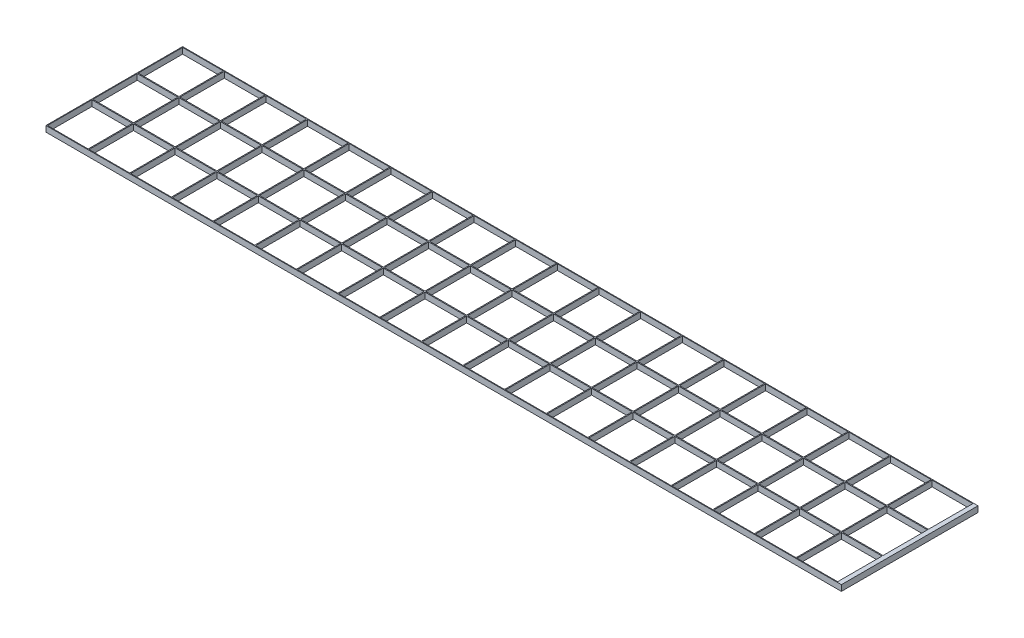
SolidWorks part; units mm, degrees
ref_plane "Front Plane" through (0, 0, 0) normal (0, 0, 1) x (1, 0, 0)
ref_plane "Top Plane" through (0, 0, 0) normal (0, 1, 0) x (1, 0, 0)
ref_plane "Right Plane" through (0, 0, 0) normal (1, 0, 0) x (0, 0, -1)
sketch "Sketch1" plane through (0, 0, 0) normal (0, 1, 0) x (1, 0, 0)
  line L1 (0, 0) -> (431.8, 0)
  line L2 (0, 0) -> (0, 74.168)
  line L3 (0, 74.168) -> (431.8, 74.168)
  line L4 (431.8, 0) -> (431.8, 74.168)
  dimension "D1" = 431.8
  dimension "D2" = 74.168
extrude "Boss-Extrude1" add sketch "Sketch1" along normal blind 3.175
sketch "Sketch2" plane through (0, 3.175, 0) normal (0, 1, 0) x (1, 0, 0)
  line L0 (431.8, 74.168) -> (0, 74.168) construction
  line L1 (0.381, 73.787) -> (22.479, 73.787)
  line L2 (0.381, 73.787) -> (0.381, 49.657)
  line L3 (0.381, 49.657) -> (22.479, 49.657)
  line L4 (22.479, 73.787) -> (22.479, 49.657)
  line L5 (0, 74.168) -> (0, 0) construction
  line L6 (0.381, 25.019) -> (22.479, 25.019)
  line L7 (22.479, 49.149) -> (22.479, 25.019)
  line L8 (0.381, 49.149) -> (0.381, 25.019)
  line L9 (0.381, 49.149) -> (22.479, 49.149)
  line L10 (0.381, 0.381) -> (22.479, 0.381)
  line L11 (22.479, 24.511) -> (22.479, 0.381)
  line L12 (0.381, 24.511) -> (0.381, 0.381)
  line L13 (0.381, 24.511) -> (22.479, 24.511)
  line L14 (22.987, 49.657) -> (45.085, 49.657)
  line L15 (45.085, 73.787) -> (45.085, 49.657)
  line L16 (22.987, 73.787) -> (22.987, 49.657)
  line L17 (22.987, 73.787) -> (45.085, 73.787)
  line L18 (22.987, 49.149) -> (22.987, 25.019)
  line L19 (45.085, 49.149) -> (45.085, 25.019)
  line L20 (22.987, 49.149) -> (45.085, 49.149)
  line L21 (22.987, 25.019) -> (45.085, 25.019)
  line L22 (22.987, 24.511) -> (45.085, 24.511)
  line L23 (22.987, 24.511) -> (22.987, 0.381)
  line L24 (45.085, 24.511) -> (45.085, 0.381)
  line L25 (22.987, 0.381) -> (45.085, 0.381)
  line L26 (45.593, 49.657) -> (67.691, 49.657)
  line L27 (67.691, 73.787) -> (67.691, 49.657)
  line L28 (45.593, 73.787) -> (45.593, 49.657)
  line L29 (45.593, 73.787) -> (67.691, 73.787)
  line L30 (45.593, 49.149) -> (45.593, 25.019)
  line L31 (67.691, 49.149) -> (67.691, 25.019)
  line L32 (45.593, 49.149) -> (67.691, 49.149)
  line L33 (45.593, 25.019) -> (67.691, 25.019)
  line L34 (45.593, 24.511) -> (67.691, 24.511)
  line L35 (45.593, 24.511) -> (45.593, 0.381)
  line L36 (67.691, 24.511) -> (67.691, 0.381)
  line L37 (45.593, 0.381) -> (67.691, 0.381)
  line L38 (68.199, 49.657) -> (90.297, 49.657)
  line L39 (90.297, 73.787) -> (90.297, 49.657)
  line L40 (68.199, 73.787) -> (68.199, 49.657)
  line L41 (68.199, 73.787) -> (90.297, 73.787)
  line L42 (68.199, 49.149) -> (68.199, 25.019)
  line L43 (90.297, 49.149) -> (90.297, 25.019)
  line L44 (68.199, 49.149) -> (90.297, 49.149)
  line L45 (68.199, 25.019) -> (90.297, 25.019)
  line L46 (68.199, 24.511) -> (90.297, 24.511)
  line L47 (68.199, 24.511) -> (68.199, 0.381)
  line L48 (90.297, 24.511) -> (90.297, 0.381)
  line L49 (68.199, 0.381) -> (90.297, 0.381)
  line L50 (90.805, 49.657) -> (112.903, 49.657)
  line L51 (112.903, 73.787) -> (112.903, 49.657)
  line L52 (90.805, 73.787) -> (90.805, 49.657)
  line L53 (90.805, 73.787) -> (112.903, 73.787)
  line L54 (90.805, 49.149) -> (90.805, 25.019)
  line L55 (112.903, 49.149) -> (112.903, 25.019)
  line L56 (90.805, 49.149) -> (112.903, 49.149)
  line L57 (90.805, 25.019) -> (112.903, 25.019)
  line L58 (90.805, 24.511) -> (112.903, 24.511)
  line L59 (90.805, 24.511) -> (90.805, 0.381)
  line L60 (112.903, 24.511) -> (112.903, 0.381)
  line L61 (90.805, 0.381) -> (112.903, 0.381)
  line L62 (113.411, 49.657) -> (135.509, 49.657)
  line L63 (135.509, 73.787) -> (135.509, 49.657)
  line L64 (113.411, 73.787) -> (113.411, 49.657)
  line L65 (113.411, 73.787) -> (135.509, 73.787)
  line L66 (113.411, 49.149) -> (113.411, 25.019)
  line L67 (135.509, 49.149) -> (135.509, 25.019)
  line L68 (113.411, 49.149) -> (135.509, 49.149)
  line L69 (113.411, 25.019) -> (135.509, 25.019)
  line L70 (113.411, 24.511) -> (135.509, 24.511)
  line L71 (113.411, 24.511) -> (113.411, 0.381)
  line L72 (135.509, 24.511) -> (135.509, 0.381)
  line L73 (113.411, 0.381) -> (135.509, 0.381)
  line L74 (136.017, 49.657) -> (158.115, 49.657)
  line L75 (158.115, 73.787) -> (158.115, 49.657)
  line L76 (136.017, 73.787) -> (136.017, 49.657)
  line L77 (136.017, 73.787) -> (158.115, 73.787)
  line L78 (136.017, 49.149) -> (136.017, 25.019)
  line L79 (158.115, 49.149) -> (158.115, 25.019)
  line L80 (136.017, 49.149) -> (158.115, 49.149)
  line L81 (136.017, 25.019) -> (158.115, 25.019)
  line L82 (136.017, 24.511) -> (158.115, 24.511)
  line L83 (136.017, 24.511) -> (136.017, 0.381)
  line L84 (158.115, 24.511) -> (158.115, 0.381)
  line L85 (136.017, 0.381) -> (158.115, 0.381)
  line L86 (158.623, 49.657) -> (180.721, 49.657)
  line L87 (180.721, 73.787) -> (180.721, 49.657)
  line L88 (158.623, 73.787) -> (158.623, 49.657)
  line L89 (158.623, 73.787) -> (180.721, 73.787)
  line L90 (158.623, 49.149) -> (158.623, 25.019)
  line L91 (180.721, 49.149) -> (180.721, 25.019)
  line L92 (158.623, 49.149) -> (180.721, 49.149)
  line L93 (158.623, 25.019) -> (180.721, 25.019)
  line L94 (158.623, 24.511) -> (180.721, 24.511)
  line L95 (158.623, 24.511) -> (158.623, 0.381)
  line L96 (180.721, 24.511) -> (180.721, 0.381)
  line L97 (158.623, 0.381) -> (180.721, 0.381)
  line L98 (181.229, 49.657) -> (203.327, 49.657)
  line L99 (203.327, 73.787) -> (203.327, 49.657)
  line L100 (181.229, 73.787) -> (181.229, 49.657)
  line L101 (181.229, 73.787) -> (203.327, 73.787)
  line L102 (181.229, 49.149) -> (181.229, 25.019)
  line L103 (203.327, 49.149) -> (203.327, 25.019)
  line L104 (181.229, 49.149) -> (203.327, 49.149)
  line L105 (181.229, 25.019) -> (203.327, 25.019)
  line L106 (181.229, 24.511) -> (203.327, 24.511)
  line L107 (181.229, 24.511) -> (181.229, 0.381)
  line L108 (203.327, 24.511) -> (203.327, 0.381)
  line L109 (181.229, 0.381) -> (203.327, 0.381)
  line L110 (203.835, 49.657) -> (225.933, 49.657)
  line L111 (225.933, 73.787) -> (225.933, 49.657)
  line L112 (203.835, 73.787) -> (203.835, 49.657)
  line L113 (203.835, 73.787) -> (225.933, 73.787)
  line L114 (203.835, 49.149) -> (203.835, 25.019)
  line L115 (225.933, 49.149) -> (225.933, 25.019)
  line L116 (203.835, 49.149) -> (225.933, 49.149)
  line L117 (203.835, 25.019) -> (225.933, 25.019)
  line L118 (203.835, 24.511) -> (225.933, 24.511)
  line L119 (203.835, 24.511) -> (203.835, 0.381)
  line L120 (225.933, 24.511) -> (225.933, 0.381)
  line L121 (203.835, 0.381) -> (225.933, 0.381)
  line L122 (226.441, 49.657) -> (248.539, 49.657)
  line L123 (248.539, 73.787) -> (248.539, 49.657)
  line L124 (226.441, 73.787) -> (226.441, 49.657)
  line L125 (226.441, 73.787) -> (248.539, 73.787)
  line L126 (226.441, 49.149) -> (226.441, 25.019)
  line L127 (248.539, 49.149) -> (248.539, 25.019)
  line L128 (226.441, 49.149) -> (248.539, 49.149)
  line L129 (226.441, 25.019) -> (248.539, 25.019)
  line L130 (226.441, 24.511) -> (248.539, 24.511)
  line L131 (226.441, 24.511) -> (226.441, 0.381)
  line L132 (248.539, 24.511) -> (248.539, 0.381)
  line L133 (226.441, 0.381) -> (248.539, 0.381)
  line L134 (249.047, 49.657) -> (271.145, 49.657)
  line L135 (271.145, 73.787) -> (271.145, 49.657)
  line L136 (249.047, 73.787) -> (249.047, 49.657)
  line L137 (249.047, 73.787) -> (271.145, 73.787)
  line L138 (249.047, 49.149) -> (249.047, 25.019)
  line L139 (271.145, 49.149) -> (271.145, 25.019)
  line L140 (249.047, 49.149) -> (271.145, 49.149)
  line L141 (249.047, 25.019) -> (271.145, 25.019)
  line L142 (249.047, 24.511) -> (271.145, 24.511)
  line L143 (249.047, 24.511) -> (249.047, 0.381)
  line L144 (271.145, 24.511) -> (271.145, 0.381)
  line L145 (249.047, 0.381) -> (271.145, 0.381)
  line L146 (271.653, 49.657) -> (293.751, 49.657)
  line L147 (293.751, 73.787) -> (293.751, 49.657)
  line L148 (271.653, 73.787) -> (271.653, 49.657)
  line L149 (271.653, 73.787) -> (293.751, 73.787)
  line L150 (271.653, 49.149) -> (271.653, 25.019)
  line L151 (293.751, 49.149) -> (293.751, 25.019)
  line L152 (271.653, 49.149) -> (293.751, 49.149)
  line L153 (271.653, 25.019) -> (293.751, 25.019)
  line L154 (271.653, 24.511) -> (293.751, 24.511)
  line L155 (271.653, 24.511) -> (271.653, 0.381)
  line L156 (293.751, 24.511) -> (293.751, 0.381)
  line L157 (271.653, 0.381) -> (293.751, 0.381)
  line L158 (294.259, 49.657) -> (316.357, 49.657)
  line L159 (316.357, 73.787) -> (316.357, 49.657)
  line L160 (294.259, 73.787) -> (294.259, 49.657)
  line L161 (294.259, 73.787) -> (316.357, 73.787)
  line L162 (294.259, 49.149) -> (294.259, 25.019)
  line L163 (316.357, 49.149) -> (316.357, 25.019)
  line L164 (294.259, 49.149) -> (316.357, 49.149)
  line L165 (294.259, 25.019) -> (316.357, 25.019)
  line L166 (294.259, 24.511) -> (316.357, 24.511)
  line L167 (294.259, 24.511) -> (294.259, 0.381)
  line L168 (316.357, 24.511) -> (316.357, 0.381)
  line L169 (294.259, 0.381) -> (316.357, 0.381)
  line L170 (316.865, 49.657) -> (338.963, 49.657)
  line L171 (338.963, 73.787) -> (338.963, 49.657)
  line L172 (316.865, 73.787) -> (316.865, 49.657)
  line L173 (316.865, 73.787) -> (338.963, 73.787)
  line L174 (316.865, 49.149) -> (316.865, 25.019)
  line L175 (338.963, 49.149) -> (338.963, 25.019)
  line L176 (316.865, 49.149) -> (338.963, 49.149)
  line L177 (316.865, 25.019) -> (338.963, 25.019)
  line L178 (316.865, 24.511) -> (338.963, 24.511)
  line L179 (316.865, 24.511) -> (316.865, 0.381)
  line L180 (338.963, 24.511) -> (338.963, 0.381)
  line L181 (316.865, 0.381) -> (338.963, 0.381)
  line L182 (339.471, 49.657) -> (361.569, 49.657)
  line L183 (361.569, 73.787) -> (361.569, 49.657)
  line L184 (339.471, 73.787) -> (339.471, 49.657)
  line L185 (339.471, 73.787) -> (361.569, 73.787)
  line L186 (339.471, 49.149) -> (339.471, 25.019)
  line L187 (361.569, 49.149) -> (361.569, 25.019)
  line L188 (339.471, 49.149) -> (361.569, 49.149)
  line L189 (339.471, 25.019) -> (361.569, 25.019)
  line L190 (339.471, 24.511) -> (361.569, 24.511)
  line L191 (339.471, 24.511) -> (339.471, 0.381)
  line L192 (361.569, 24.511) -> (361.569, 0.381)
  line L193 (339.471, 0.381) -> (361.569, 0.381)
  line L194 (362.077, 49.657) -> (384.175, 49.657)
  line L195 (384.175, 73.787) -> (384.175, 49.657)
  line L196 (362.077, 73.787) -> (362.077, 49.657)
  line L197 (362.077, 73.787) -> (384.175, 73.787)
  line L198 (362.077, 49.149) -> (362.077, 25.019)
  line L199 (384.175, 49.149) -> (384.175, 25.019)
  line L200 (362.077, 49.149) -> (384.175, 49.149)
  line L201 (362.077, 25.019) -> (384.175, 25.019)
  line L202 (362.077, 24.511) -> (384.175, 24.511)
  line L203 (362.077, 24.511) -> (362.077, 0.381)
  line L204 (384.175, 24.511) -> (384.175, 0.381)
  line L205 (362.077, 0.381) -> (384.175, 0.381)
  line L206 (384.683, 49.657) -> (406.781, 49.657)
  line L207 (406.781, 73.787) -> (406.781, 49.657)
  line L208 (384.683, 73.787) -> (384.683, 49.657)
  line L209 (384.683, 73.787) -> (406.781, 73.787)
  line L210 (384.683, 49.149) -> (384.683, 25.019)
  line L211 (406.781, 49.149) -> (406.781, 25.019)
  line L212 (384.683, 49.149) -> (406.781, 49.149)
  line L213 (384.683, 25.019) -> (406.781, 25.019)
  line L214 (384.683, 24.511) -> (406.781, 24.511)
  line L215 (384.683, 24.511) -> (384.683, 0.381)
  line L216 (406.781, 24.511) -> (406.781, 0.381)
  line L217 (384.683, 0.381) -> (406.781, 0.381)
  line L218 (407.289, 49.657) -> (429.387, 49.657)
  line L219 (429.387, 73.787) -> (429.387, 49.657)
  line L220 (407.289, 73.787) -> (407.289, 49.657)
  line L221 (407.289, 73.787) -> (429.387, 73.787)
  line L222 (407.289, 49.149) -> (407.289, 25.019)
  line L223 (429.387, 49.149) -> (429.387, 25.019)
  line L224 (407.289, 49.149) -> (429.387, 49.149)
  line L225 (407.289, 25.019) -> (429.387, 25.019)
  line L226 (407.289, 24.511) -> (429.387, 24.511)
  line L227 (407.289, 24.511) -> (407.289, 0.381)
  line L228 (429.387, 24.511) -> (429.387, 0.381)
  line L229 (407.289, 0.381) -> (429.387, 0.381)
  dimension "D1" = 24.13
  dimension "D2" = 0.381
  dimension "D3" = 0.381
  dimension "D4" = 22.098
  dimension "D7" = 0.508
  dimension "D5" = 3
  dimension "D6" = 19
extrude "Cut-Extrude1" cut sketch "Sketch2" against normal blind 3.175
